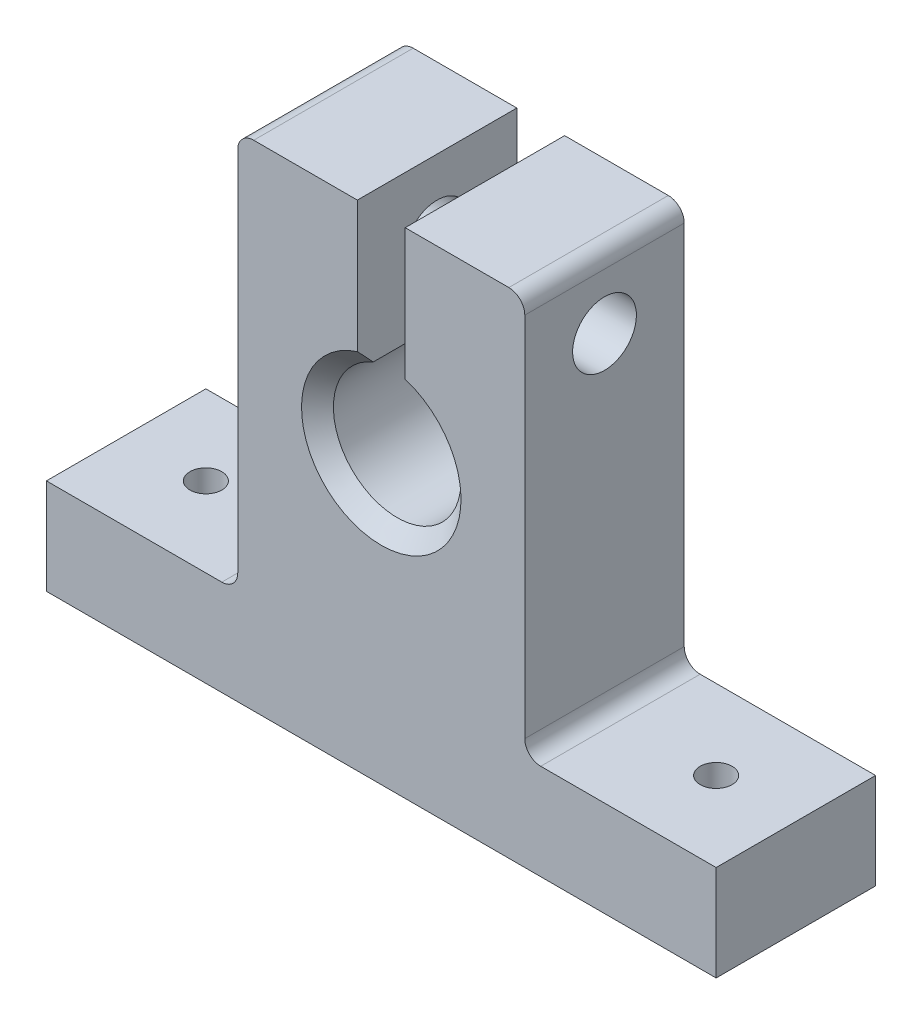
SolidWorks part; units mm, degrees
ref_plane "Front Plane" through (0, 0, 0) normal (0, 0, 1) x (1, 0, 0)
ref_plane "Top Plane" through (0, 0, 0) normal (0, 1, 0) x (1, 0, 0)
ref_plane "Right Plane" through (0, 0, 0) normal (1, 0, 0) x (0, 0, -1)
sketch "Sketch1" plane through (0, 0, 0) normal (0, 0, 1) x (1, 0, 0)
  line L1 (-21, -3) -> (21, -3)
  line L2 (-21, -3) -> (-21, 3)
  line L3 (-21, 3) -> (21, 3)
  line L4 (21, -3) -> (21, 3)
  line L5 (-21, -3) -> (21, 3) construction
  line L6 (-21, 3) -> (21, -3) construction
  point P0 (0, 0)
  dimension "D1" = 42
  dimension "D2" = 6
extrude "Boss-Extrude1" add sketch "Sketch1" along normal blind 14
sketch "Sketch2" plane through (0, 0, 14) normal (0, 0, 1) x (1, 0, 0)
  line L0 (0, 0) -> (0, 28) construction
  line L1 (0, 28) -> (-9, 28)
  line L2 (-9, 28) -> (-9, 3)
  line L3 (21, 3) -> (-21, 3) construction
  line L4 (0, 28) -> (9, 28)
  line L5 (9, 28) -> (9, 3)
  line L6 (9, 3) -> (-9, 3)
  dimension "D1" = 9
  dimension "D2" = 9
  dimension "D3" = 25
extrude "Boss-Extrude2" add sketch "Sketch2" against normal blind 14
sketch "Sketch3" plane through (0, 0, 14) normal (0, 0, 1) x (1, 0, 0)
  line L0 (0, -3) -> (0, 33.9088) construction
  line L1 (-21, -3) -> (21, -3) construction
  circle A0 centre (0, 15) radius 4
  dimension "D1" = 8
  dimension "D2" = 18
extrude "Cut-Extrude1" cut sketch "Sketch3" against normal blind 14
sketch "Sketch4" plane through (0, -3, 0) normal (0, -1, 0) x (1, 0, 0)
  line L0 (0, 14) -> (0, 0) construction
  line L1 (-21, 14) -> (21, 14) construction
  line L2 (-21, 7) -> (21, 7) construction
  line L3 (-21, 14) -> (-21, 0) construction
  line L4 (21, 14) -> (21, 0) construction
  circle A0 centre (-16, 7) radius 1
  circle A1 centre (16, 7) radius 1
  dimension "D3" = 2
  dimension "D4" = 2
  dimension "D1" = 16
  dimension "D2" = 16
extrude "Cut-Extrude2" cut sketch "Sketch4" against normal blind 14
fillet "Fillet1" radius 1 1 edges at (-9, 3, 7)
fillet "Fillet2" radius 1 1 edges at (9, 3, 7)
fillet "Fillet3" radius 1 1 edges at (-9, 28, 7)
fillet "Fillet4" radius 1 1 edges at (9, 28, 7)
chamfer "Chamfer1" distance 1 angle 45 1 edges at (4, 15, 14)
chamfer "Chamfer2" distance 1 angle 45 1 edges at (4, 15, 0)
sketch "Sketch6" plane through (0, 0, 14) normal (0, 0, 1) x (1, 0, 0)
  line L0 (0, -3) -> (0, 38.3219) construction
  line L1 (-21, -3) -> (21, -3) construction
  line L2 (0, 28) -> (-1.5, 28)
  line L3 (8, 28) -> (-8, 28) construction
  line L4 (-1.5, 28) -> (-1.5, 18.7081)
  line L5 (0, 28) -> (1.5, 28)
  line L6 (1.5, 28) -> (1.5, 18.7081)
  circle A0 centre (0, 15) radius 4 construction
  arc A1 (1.5, 18.7081) -> (-1.5, 18.7081) centre (0, 15) ccw
  dimension "D1" = 1.5
  dimension "D2" = 1.5
extrude "Cut-Extrude4" cut sketch "Sketch6" against normal blind 14
sketch "Sketch7" plane through (9, 0, 0) normal (1, 0, 0) x (0, 0, -1)
  line L0 (-14, -3) -> (0, -3) construction
  line L1 (0, 27) -> (-14, 27) construction
  circle A0 centre (-7, 23.5) radius 2
  point P5 (-7, -3)
  point P9 (-7, 27)
  dimension "D1" = 4
  dimension "D2" = 3.5
extrude "Cut-Extrude5" cut sketch "Sketch7" against normal blind 24
sketch "Sketch10" plane through (0, 0, 14) normal (0, 0, 1) x (1, 0, 0)
  line L1 (-30.9473, 36.1576) -> (32.9539, 36.1576)
  line L2 (-30.9473, 36.1576) -> (-30.9473, -7.8214)
  line L3 (-30.9473, -7.8214) -> (32.9539, -7.8214)
  line L4 (32.9539, 36.1576) -> (32.9539, -7.8214)
extrude "Cut-Extrude8" cut sketch "Sketch10" against normal blind 2
sketch "Sketch11" plane through (0, 0, 0) normal (0, 0, -1) x (-1, 0, 0)
  line L1 (-28.3245, 36.0088) -> (34.5483, 36.0088)
  line L2 (-28.3245, 36.0088) -> (-28.3245, -8.7007)
  line L3 (-28.3245, -8.7007) -> (34.5483, -8.7007)
  line L4 (34.5483, 36.0088) -> (34.5483, -8.7007)
extrude "Cut-Extrude9" cut sketch "Sketch11" against normal blind 2
chamfer "Chamfer3" distance 1 angle 45 1 edges at (0, 11, 12)
chamfer "Chamfer4" distance 1 angle 45 1 edges at (0, 11, 2)
